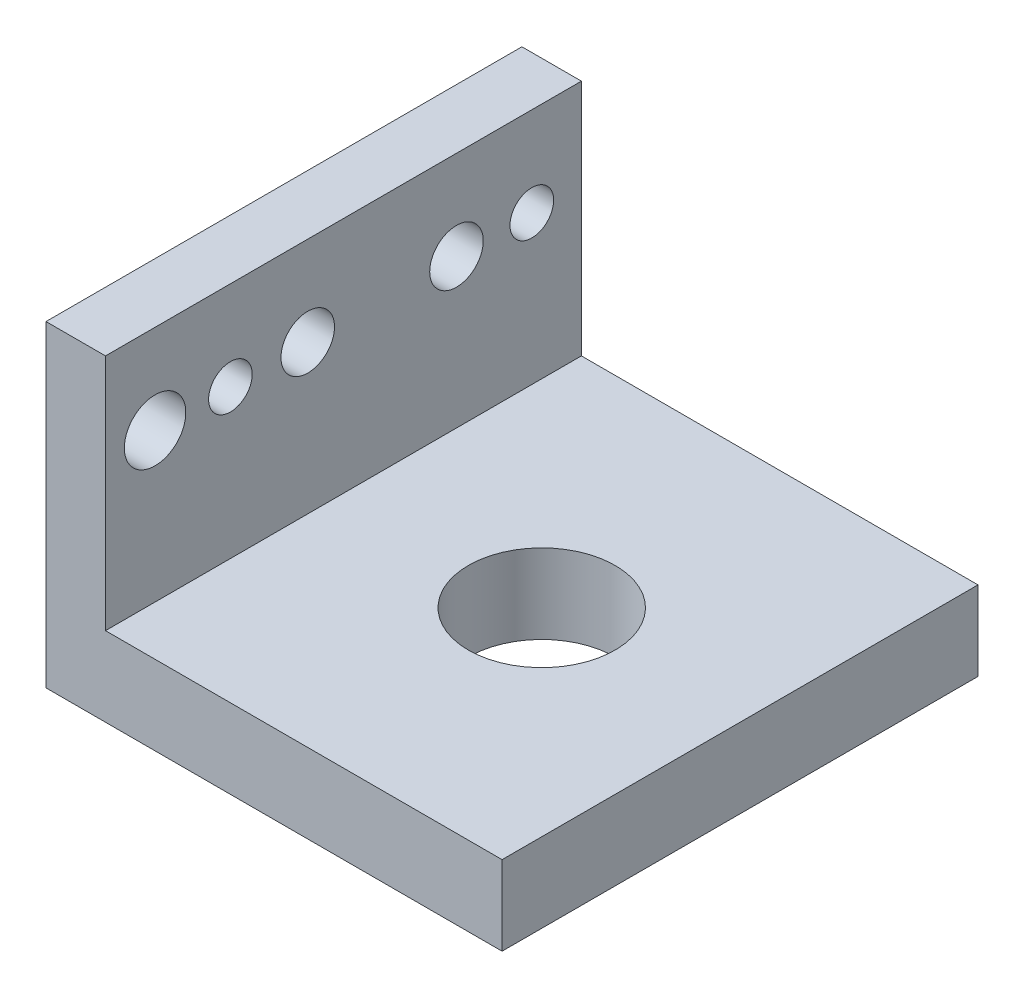
SolidWorks part; units mm, degrees
ref_plane "前视基准面" through (0, 0, 0) normal (0, 0, 1) x (1, 0, 0)
ref_plane "上视基准面" through (0, 0, 0) normal (0, 1, 0) x (1, 0, 0)
ref_plane "右视基准面" through (0, 0, 0) normal (1, 0, 0) x (0, 0, -1)
other "Configuration Table"
sketch "草图1" plane through (0, 0, 0) normal (0, 1, 0) x (1, 0, 0)
  line L0 (20, 12) -> (10, 12) construction
  line L1 (0, 0) -> (20, 0)
  line L2 (0, 0) -> (0, 24)
  line L3 (0, 24) -> (20, 24)
  line L4 (20, 0) -> (20, 24)
  line L5 (10, 12) -> (10, 24) construction
  circle A0 centre (10, 12) radius 3.7
  point P7 (10, 24)
  dimension "D2" = 7.4
  dimension "D1" = 20
  dimension "D3" = 24
extrude "凸台-拉伸1" add sketch "草图1" along normal blind 4
sketch "草图2" plane through (0, 0, 0) normal (-1, 0, 0) x (0, 0, 1)
  line L0 (-24, 0) -> (-24, 16)
  line L1 (-24, 16) -> (0, 16)
  line L2 (0, 16) -> (0, 0)
  line L3 (-24, 11.5) -> (0, 11.5) construction
  line L4 (-24, 0) -> (0, 0)
  line L5 (0, 0) -> (0, 4)
  line L6 (0, 4) -> (-24, 4)
  line L7 (-24, 4) -> (-24, 0)
  line L8 (-24, 0) -> (0, 0)
  line L9 (0, 0) -> (0, 4) construction
  line L10 (0, 4) -> (-24, 4) construction
  line L11 (-24, 4) -> (-24, 0) construction
  circle A0 centre (-21.5, 11.5) radius 1.1
  circle A1 centre (-17.7, 11.5) radius 1.35
  circle A2 centre (-6.3, 11.5) radius 1.1
  circle A3 centre (-2.5, 11.5) radius 1.55
  circle A4 centre (-10.2, 11.5) radius 1.35
  dimension "D4" = 2.2
  dimension "D5" = 2.7
  dimension "D6" = 3.1
  dimension "D7" = 2.2
  dimension "D12" = 2.7
  dimension "D2" = 12
  dimension "D3" = 4.5
  dimension "D8" = 2.5
  dimension "D9" = 3.8
  dimension "D10" = 2.5
  dimension "D11" = 3.8
  dimension "D13" = 3.9
  dimension "D1" = 0
extrude "凸台-拉伸2" add sketch "草图2" along normal blind 3
